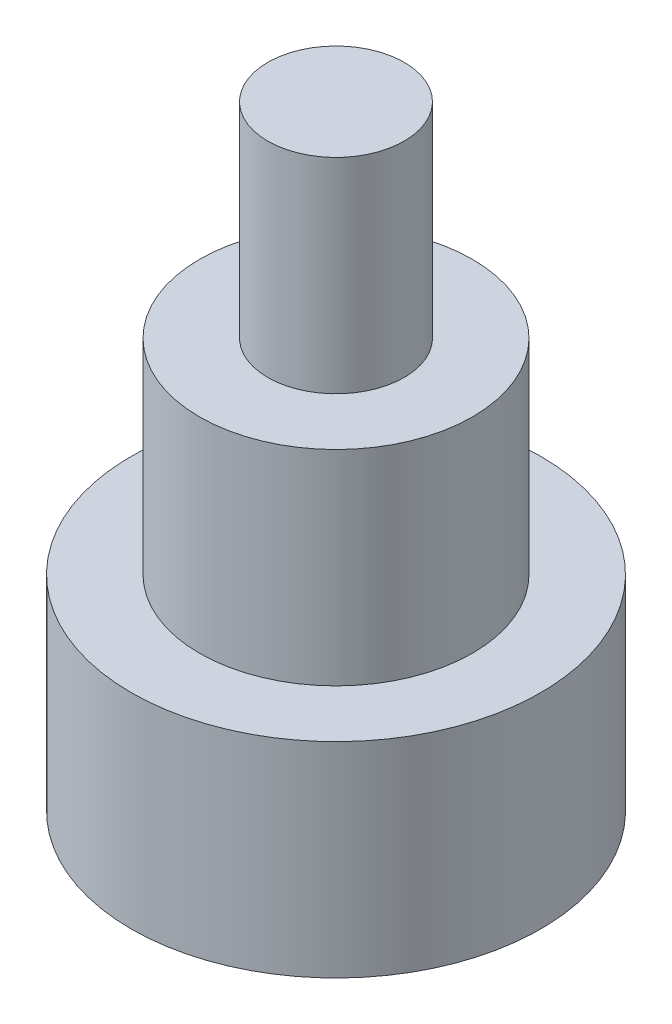
SolidWorks part; units mm, degrees
ref_plane "정면" through (0, 0, 0) normal (0, 0, 1) x (1, 0, 0)
ref_plane "윗면" through (0, 0, 0) normal (0, 1, 0) x (1, 0, 0)
ref_plane "우측면" through (0, 0, 0) normal (1, 0, 0) x (0, 0, -1)
sketch "스케치1" plane through (0, 0, 0) normal (0, 1, 0) x (1, 0, 0)
  circle A0 centre (-14.0949, 0.9235) radius 30
  dimension "D1" = 60
extrude "보스-돌출1" add sketch "스케치1" along normal blind 30
sketch "스케치2" plane through (0, 30, 0) normal (0, 1, 0) x (1, 0, 0)
  circle A0 centre (-14.0949, 0.9235) radius 20
extrude "보스-돌출2" add sketch "스케치2" along normal blind 30
sketch "스케치3" plane through (0, 60, 0) normal (0, 1, 0) x (1, 0, 0)
  circle A0 centre (-14.0949, 0.9235) radius 10
extrude "보스-돌출3" add sketch "스케치3" along normal blind 30
